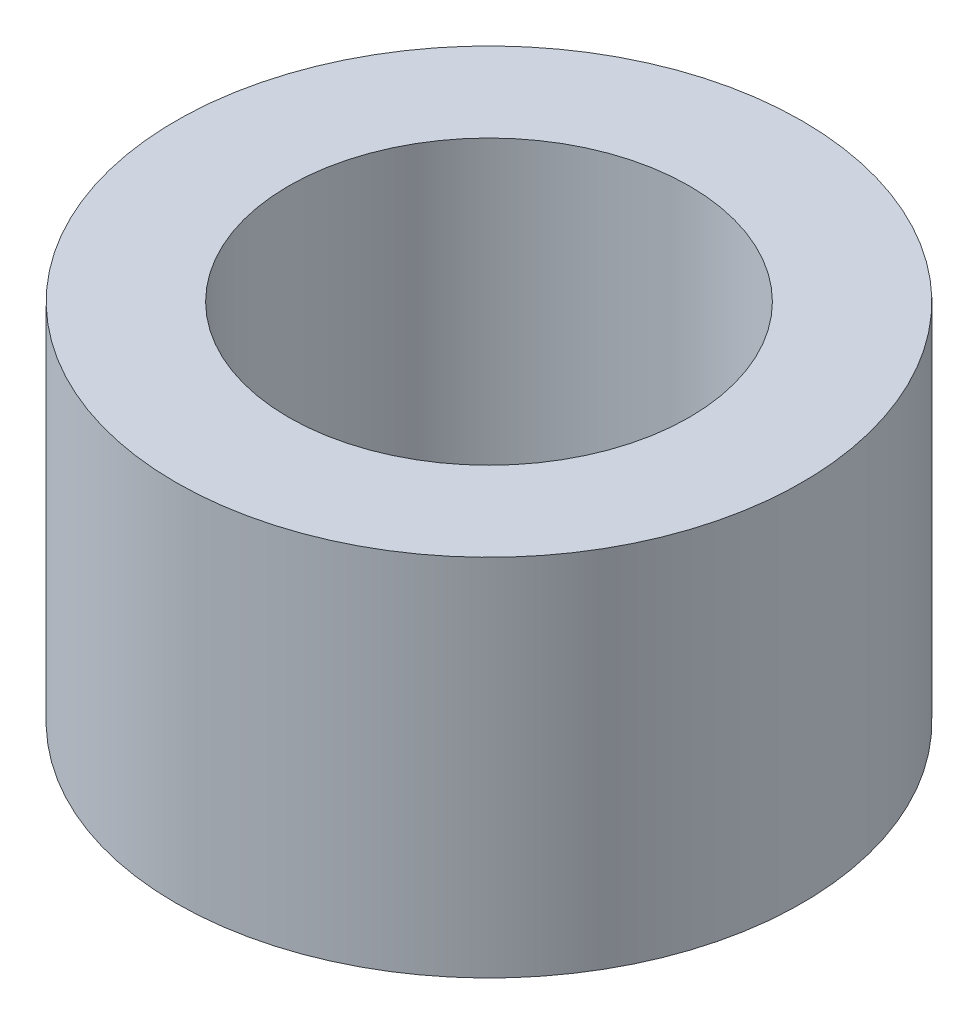
SolidWorks part; units mm, degrees
ref_plane "前视基准面" through (0, 0, 0) normal (0, 0, 1) x (1, 0, 0)
ref_plane "上视基准面" through (0, 0, 0) normal (0, 1, 0) x (1, 0, 0)
ref_plane "右视基准面" through (0, 0, 0) normal (1, 0, 0) x (0, 0, -1)
sketch "草图1" plane through (0, 0, 0) normal (0, 1, 0) x (1, 0, 0)
  circle A0 centre (0, 0) radius 1.65
  circle A1 centre (0, 0) radius 2.5781
  dimension "D1" = 3.3
extrude "凸台-拉伸1" add sketch "草图1" along normal blind 3
